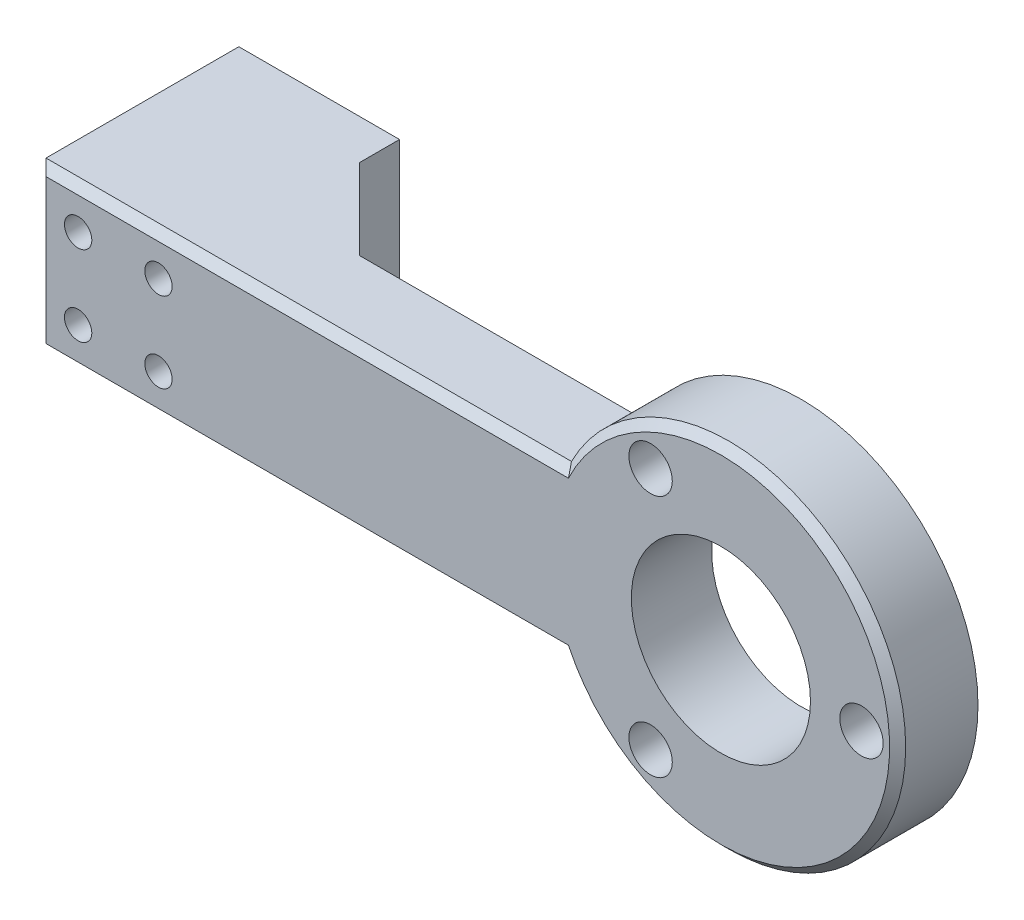
SolidWorks part; units mm, degrees
ref_plane "正面" through (0, 0, 0) normal (0, 0, 1) x (1, 0, 0)
ref_plane "平面" through (0, 0, 0) normal (0, 1, 0) x (1, 0, 0)
ref_plane "右側面" through (0, 0, 0) normal (1, 0, 0) x (0, 0, -1)
sketch "ｽｹｯﾁ1" plane through (0, 0, 0) normal (0, 0, 1) x (1, 0, 0)
  circle A0 centre (0, 0) radius 11.15
  circle A2 centre (-8.75, -15.1554) radius 2.7 construction
  circle A3 centre (0, 0) radius 22
  circle A4 centre (0, 0) radius 22
  circle A5 centre (17.5, 0) radius 2.7 construction
  circle A6 centre (-8.75, 15.1554) radius 2.7 construction
  circle A7 centre (-8.75, -15.1554) radius 2.7
  circle A8 centre (17.5, 0) radius 2.7
  circle A9 centre (-8.75, 15.1554) radius 2.7
  dimension "D1" = 22.3
  dimension "D2" = 0
extrude "ﾎﾞｽ - 押し出し1" add sketch "ｽｹｯﾁ1" along normal blind 10
sketch "ｽｹｯﾁ2" plane through (0, 0, 10) normal (0, 0, 1) x (1, 0, 0)
  line L0 (0, 0) -> (-85, 0) construction
  line L1 (0, 22) -> (-85, 22)
  line L2 (0, -22) -> (-85, -22)
  line L3 (0, 0) -> (-85, 0) construction
  line L4 (-85, 22) -> (-85, -22)
  circle A0 centre (0, 0) radius 22 construction
  circle A1 centre (0, 0) radius 22
  circle M5 centre (0, 0) radius 22
  dimension "D3" = 85
  dimension "D1" = 22
extrude "ﾎﾞｽ - 押し出し2" add sketch "ｽｹｯﾁ2" against normal blind 10 contours L1 L4 L2 M5
sketch "ｽｹｯﾁ3" plane through (0, 0, 10) normal (0, 0, 1) x (1, 0, 0)
  line L0 (-85, 0) -> (-58.1456, 0) construction
  line L1 (-85, 22) -> (-85, -22) construction
  line L2 (-85, 10) -> (4, 10)
  line L5 (0, 22) -> (-85, 22)
  line L6 (-85, 22) -> (-85, -22)
  line L7 (-85, -22) -> (0, -22)
  line L8 (0, 22) -> (-85, 22)
  line L9 (-85, 22) -> (-85, -22)
  line L10 (-85, -22) -> (0, -22)
  line L11 (-85, -10) -> (4, -10)
  circle A0 centre (0, 0) radius 22
  arc A1 (0, -22) -> (0, 22) centre (0, 0) ccw
  arc A2 (0, -22) -> (0, 22) centre (0, 0) ccw
  dimension "D4" = 44
  dimension "D2" = 89
  dimension "D3" = 10
  dimension "D1" = 0
extrude "ｶｯﾄ - 押し出し1" cut sketch "ｽｹｯﾁ3" against normal blind 10
sketch "ｽｹｯﾁ4" plane through (0, 0, 0) normal (0, 0, -1) x (-1, 0, 0)
  line L0 (85, 10) -> (85, -10) construction
  line L1 (85, -10) -> (65, -10)
  line L2 (85, -10) -> (85, 10)
  line L3 (85, 10) -> (65, 10)
  line L4 (65, -10) -> (65, 10)
  line L5 (85, 10) -> (19.5959, 10) construction
  dimension "D1" = 65
extrude "ﾎﾞｽ - 押し出し3" add sketch "ｽｹｯﾁ4" along normal blind 15
chamfer "面取り2" distance 10 angle 45 1 edges at (-65, 0, 0)
chamfer "面取り4" distance 1 angle 45 3 edges at (-52.298, -10, 10) (-52.298, 10, 10) (22, 0, 10)
sketch "ｽｹｯﾁ6" plane through (0, 0, -15) normal (0, 0, -1) x (-1, 0, 0)
  line L1 (80, 10) -> (80, 5) construction
  line L2 (85, 10) -> (65, 10) construction
  line L3 (85, -10) -> (85, 10) construction
  line L4 (75, 10) -> (75, -10) construction
  line L5 (65, -10) -> (85, -10) construction
  line L6 (85, 0) -> (65, 0) construction
  circle A0 centre (80, 5) radius 1.7
  circle A1 centre (70, 5) radius 1.7
  circle A2 centre (70, -5) radius 1.7
  circle A3 centre (80, -5) radius 1.7
  dimension "D1" = 3.4
  dimension "D2" = 5
  dimension "D3" = 5
extrude "ｶｯﾄ - 押し出し3" cut sketch "ｽｹｯﾁ6" against normal through all
chamfer "面取り6" distance 1 angle 45 1 edges at (-85, 0, 10)
